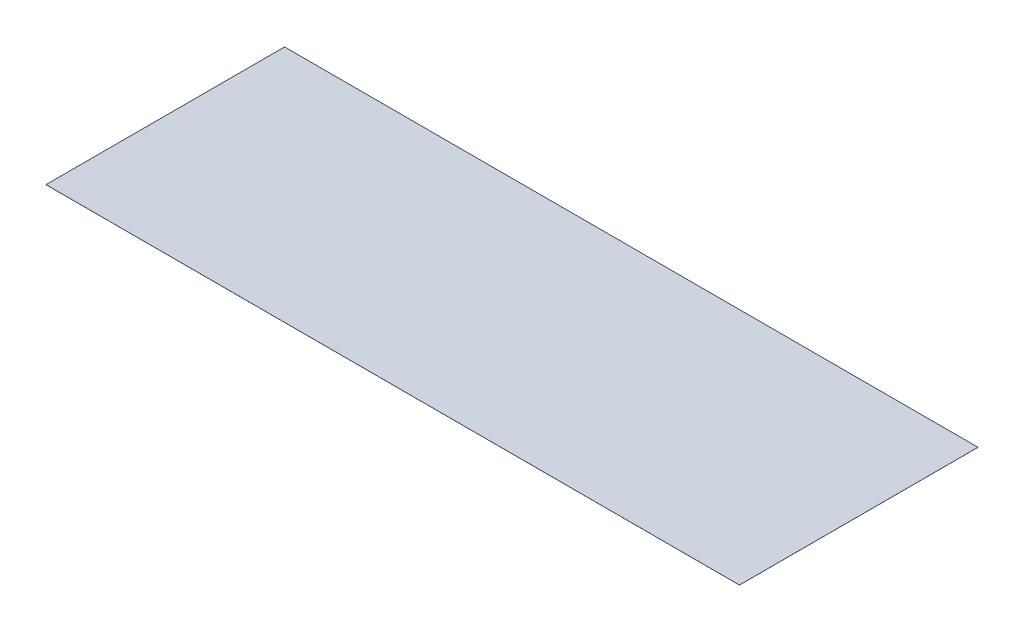
SolidWorks part; units mm, degrees
ref_plane "Front Plane" through (0, 0, 0) normal (0, 0, 1) x (1, 0, 0)
ref_plane "Top Plane" through (0, 0, 0) normal (0, 1, 0) x (1, 0, 0)
ref_plane "Right Plane" through (0, 0, 0) normal (1, 0, 0) x (0, 0, -1)
sketch "Sketch2" plane through (0, 0, 0) normal (0, 1, 0) x (1, 0, 0)
  line L1 (-675.5029, 259.4952) -> (16045.3682, 259.4952)
  line L2 (-675.5029, 259.4952) -> (-675.5029, -5492.4805)
  line L3 (-675.5029, -5492.4805) -> (16045.3682, -5492.4805)
  line L4 (16045.3682, 259.4952) -> (16045.3682, -5492.4805)
extrude "Boss-Extrude1" add sketch "Sketch2" along normal blind 1 contours L2 L1 L4 L3
